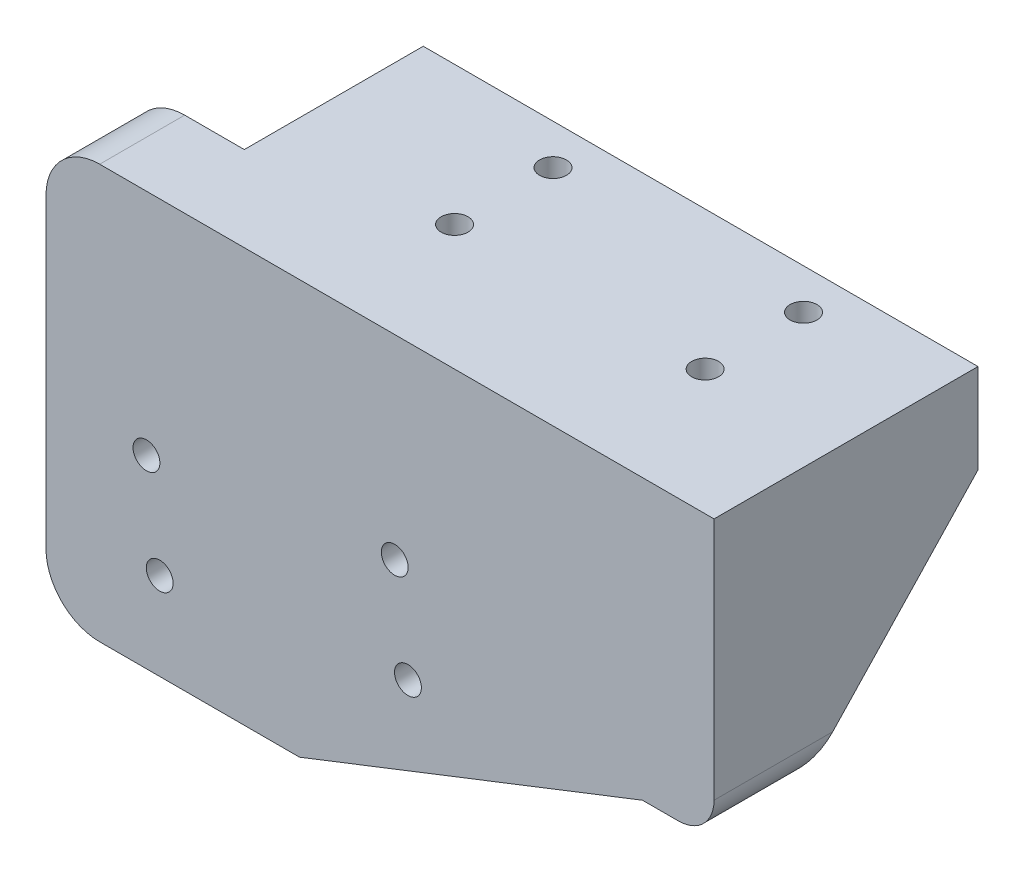
SolidWorks part; units mm, degrees
ref_plane "前视基准面" through (0, 0, 0) normal (0, 0, 1) x (1, 0, 0)
ref_plane "上视基准面" through (0, 0, 0) normal (0, 1, 0) x (1, 0, 0)
ref_plane "右视基准面" through (0, 0, 0) normal (1, 0, 0) x (0, 0, -1)
sketch "草图1" plane through (0, 0, 0) normal (0, 1, 0) x (1, 0, 0)
  line L1 (-21, -10) -> (21, -10)
  line L2 (-21, -10) -> (-21, 10)
  line L3 (-21, 10) -> (21, 10)
  line L4 (21, -10) -> (21, 10)
  line L5 (-21, -10) -> (21, 10) construction
  line L6 (-21, 10) -> (21, -10) construction
  point P0 (0, 0)
  dimension "D1" = 42
  dimension "D2" = 20
extrude "凸台-拉伸1" add sketch "草图1" along normal blind 10
sketch "草图2" plane through (0, 10, 0) normal (0, 1, 0) x (1, 0, 0)
  line L0 (0, 10) -> (0, -10) construction
  line L1 (21, 10) -> (-21, 10) construction
  line L2 (-21, -10) -> (21, -10) construction
  line L3 (-21, 0) -> (21, 0) construction
  line L4 (-21, 10) -> (-21, -10) construction
  line L5 (21, -10) -> (21, 10) construction
  circle A0 centre (-14, 5.5) radius 1.5
  circle A1 centre (14, 5.5) radius 1.5
  circle A2 centre (14, -5.5) radius 1.5
  circle A3 centre (-14, -5.5) radius 1.5
  dimension "D1" = 3
  dimension "D2" = 5.5
  dimension "D3" = 28
extrude "切除-拉伸1" cut sketch "草图2" against normal through all
sketch "草图3" plane through (0, 0, 0) normal (0, -1, 0) x (1, 0, 0)
  line L1 (-21, 10) -> (-33, 10)
  line L2 (-21, 10) -> (-21, -10)
  line L3 (-21, -10) -> (-33, -10)
  line L4 (-33, 10) -> (-33, -10)
  line L5 (-21, 10) -> (-33, -10) construction
  line L6 (-21, -10) -> (-33, 10) construction
  point P4 (-27, 0)
  dimension "D1" = 20
  dimension "D2" = 12
extrude "凸台-拉伸2" add sketch "草图3" against normal up to surface (10 mm away)
sketch "草图4" plane through (0, 0, 10) normal (0, 0, 1) x (1, 0, 0)
  line L0 (-33, 10) -> (21, 10) construction
  line L1 (21, 10) -> (-105.6644, 10)
  line L2 (21, 10) -> (21, -36.2298)
  line L3 (21, -36.2298) -> (-105.6644, -36.2298)
  line L4 (-105.6644, 10) -> (-105.6644, -36.2298)
  line L5 (21, 10) -> (-105.6644, -36.2298) construction
  line L6 (21, -36.2298) -> (-105.6644, 10) construction
  point P4 (-42.3322, -13.1149)
extrude "凸台-拉伸3" add sketch "草图4" along normal up to surface (9.5 mm away)
sketch "草图5" plane through (0, 0, 19.5) normal (0, 0, 1) x (1, 0, 0)
  circle A4 centre (-34.4356, -15.5631) radius 1.5
  circle A5 centre (-6.6896, -11.7999) radius 1.5
  circle A6 centre (-5.2112, -22.7001) radius 1.5
  circle A7 centre (-32.9572, -26.4633) radius 1.5
extrude "切除-拉伸2" cut sketch "草图5" against normal through all
sketch "草图6" plane through (0, 0, 19.5) normal (0, 0, 1) x (1, 0, 0)
  line L0 (-105.6644, 10) -> (21, 10) construction
  line L1 (-105.6644, -36.2298) -> (-45.6644, -36.2298)
  line L2 (-105.6644, -36.2298) -> (-105.6644, 10)
  line L3 (-105.6644, 10) -> (-45.6644, 10)
  line L4 (-45.6644, -36.2298) -> (-45.6644, 10)
  line L5 (-105.6644, -36.2298) -> (-45.6644, 10) construction
  line L6 (-105.6644, 10) -> (-45.6644, -36.2298) construction
  point P4 (-75.6644, -13.1149)
  dimension "D1" = 60
extrude "切除-拉伸3" cut sketch "草图6" against normal through all
sketch "草图8" plane through (21, 0, 0) normal (1, 0, 0) x (0, 0, -1)
  line L6 (-10, 0) -> (10, 0)
  line L7 (10, 0) -> (10, 10)
  line L8 (10, 10) -> (-19.5, 10)
  line L9 (-19.5, 10) -> (-19.5, -36.2298)
  line L10 (-19.5, -36.2298) -> (-10, -36.2298)
  line L11 (-10, -36.2298) -> (-10, 0)
  line L12 (-10, 0) -> (10, 0)
  line L13 (10, 0) -> (10, 10)
  line L14 (10, 10) -> (-19.5, 10)
  line L15 (-19.5, 10) -> (-19.5, -36.2298)
  line L16 (-19.5, -36.2298) -> (-10, -36.2298)
  line L17 (-10, -36.2298) -> (-10, 0)
  dimension "D1" = 0
extrude "凸台-拉伸4" add sketch "草图8" along normal blind 8
sketch "草图9" plane through (0, 0, 19.5) normal (0, 0, 1) x (1, 0, 0)
  line L0 (-8.3322, -36.2298) -> (29, -21.2298)
  line L1 (29, -36.2298) -> (-45.6644, -36.2298) construction
  line L2 (29, 10) -> (29, -36.2298) construction
  line M8 (-45.6644, -36.2298) -> (29, -36.2298)
  line M9 (29, -36.2298) -> (29, 10)
  dimension "D1" = 15
extrude "切除-拉伸4" cut sketch "草图9" against normal through all and the other way through all contours L0 M8 M9
sketch "草图10" plane through (29, 0, 0) normal (1, 0, 0) x (0, 0, -1)
  line L0 (-10, -21.2298) -> (10, 0)
rib "筋1" sketch "草图10" sketch "草图10" thickness 8 extrusion direction parallel to sketch draft on no parameters "D1"=8
sketch "草图12" plane through (0, 0, 10) normal (0, 0, -1) x (-1, 0, 0)
  line L0 (25.4217, -36.2298) -> (25.4217, -26.2298)
  line L2 (45.6644, -36.2298) -> (8.3322, -36.2298) construction
  line L3 (-21, -21.2298) -> (17.3322, -36.2298)
  line L5 (17.3322, -36.2298) -> (8.3322, -36.2298)
  line L6 (-21, -21.2298) -> (-29, -21.2298)
  line L7 (8.3322, -36.2298) -> (-29, -21.2298)
  line M9 (-21, -21.2298) -> (-29, -21.2298)
  line M10 (-29, -21.2298) -> (8.3322, -36.2298)
  line M11 (8.3322, -36.2298) -> (45.6644, -36.2298)
  dimension "D1" = 10
extrude "切除-拉伸5" cut sketch "草图12" against normal through all contours L3 M9 M10 M11
ref_plane "基准面1" through (-26.6644, 0, 0) normal (1, 0, 0) x (0, 0, -1)
sketch "草图13" plane through (-26.6644, 0, 0) normal (1, 0, 0) x (0, 0, -1)
  line L0 (-10, -36.2298) -> (10, 0)
  line L1 (10, 0) -> (-10, 0)
  line L2 (-10, 0) -> (-10, -36.2298)
extrude "凸台-拉伸5" add sketch "草图13" along normal blind 8
fillet "圆角1" radius 3 3 edges at (21, 0, 0) (-26.6644, 0, 0) (-18.6644, 0, 0)
fillet "圆角2" radius 4 1 edges at (29, -21.2298, 14.75)
fillet "圆角3" radius 6 2 edges at (-45.6644, 10, 14.75) (-45.6644, -36.2298, 14.75)
